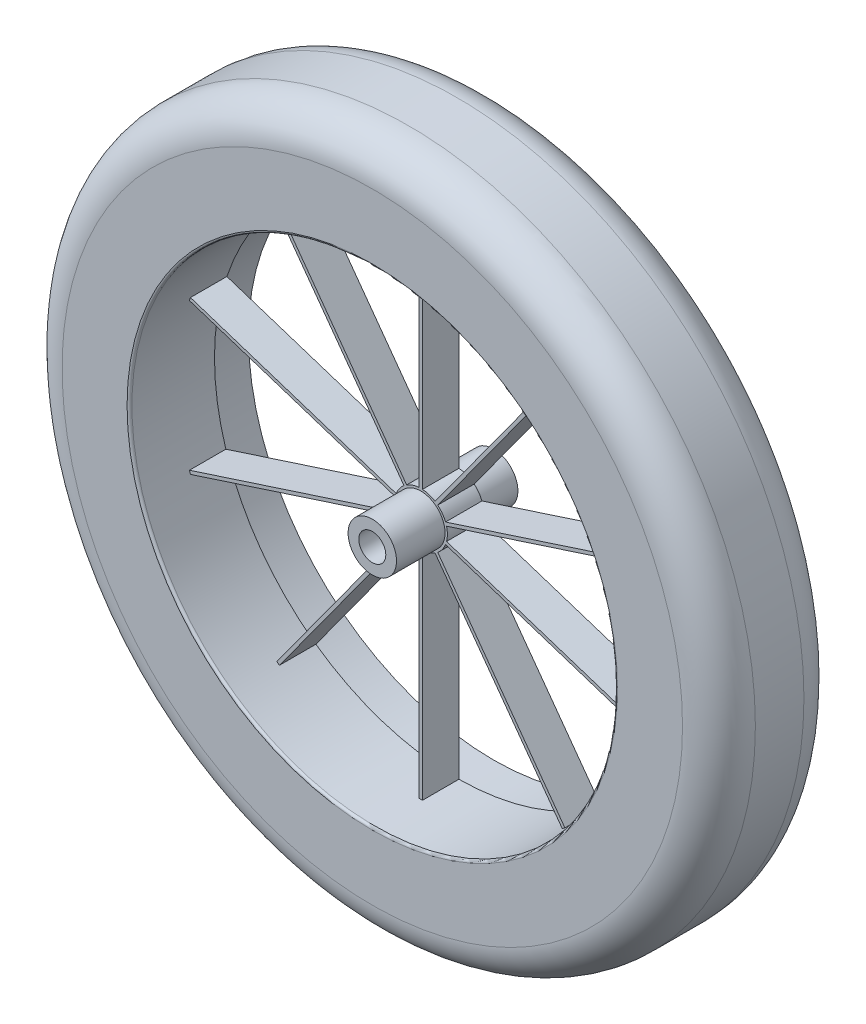
SolidWorks part; units mm, degrees
ref_plane "Alzado" through (0, 0, 0) normal (0, 0, 1) x (1, 0, 0)
ref_plane "Planta" through (0, 0, 0) normal (0, 1, 0) x (1, 0, 0)
ref_plane "Vista lateral" through (0, 0, 0) normal (1, 0, 0) x (0, 0, -1)
sketch "Croquis1" plane through (0, 0, 0) normal (0, 0, 1) x (1, 0, 0)
  circle A0 centre (0, 0) radius 275
  dimension "D1" = 550
extrude "Saliente-Extruir1" add sketch "Croquis1" along normal blind 70
sketch "Croquis2" plane through (0, 0, 70) normal (0, 0, 1) x (1, 0, 0)
  circle A0 centre (0, 0) radius 200
  dimension "D1" = 400
extrude "Cortar-Extruir1" cut sketch "Croquis2" against normal blind 40
sketch "Croquis5" plane through (0, 0, 30) normal (0, 0, 1) x (1, 0, 0)
  circle A0 centre (0, 0) radius 10
  dimension "D1" = 20
extrude "Cortar-Extruir2" cut sketch "Croquis5" against normal blind 10
fillet "Redondeo1" radius 2 1 edges at (200, 0, 70)
sketch "Croquis6" plane through (0, 0, 70) normal (0, 0, 1) x (1, 0, 0)
  line L0 (0, 275) -> (0, 247)
  line L1 (99.3415, 256.4299) -> (89.2267, 230.3206)
  line L2 (185.2663, 203.2275) -> (166.4028, 182.5352)
  line L3 (246.1699, 122.578) -> (221.1053, 110.0974)
  line L4 (273.8269, 25.3738) -> (245.9463, 22.7903)
  line L5 (264.5021, -75.2573) -> (237.5709, -67.5948)
  line L6 (219.4547, -165.7245) -> (197.1103, -148.8508)
  line L7 (144.7688, -233.8097) -> (130.0287, -210.0036)
  line L8 (50.5311, -270.3176) -> (45.3861, -242.7944)
  line L9 (-50.5311, -270.3176) -> (-45.3861, -242.7944)
  line L10 (-144.7688, -233.8097) -> (-130.0287, -210.0036)
  line L11 (-219.4547, -165.7245) -> (-197.1103, -148.8508)
  line L12 (-264.5021, -75.2573) -> (-237.5709, -67.5948)
  line L13 (-273.8269, 25.3738) -> (-245.9463, 22.7903)
  line L14 (-246.1699, 122.578) -> (-221.1053, 110.0974)
  line L15 (-185.2663, 203.2275) -> (-166.4028, 182.5352)
  line L16 (-99.3415, 256.4299) -> (-89.2267, 230.3206)
  circle A0 centre (0, 0) radius 275 construction
  point P40 (0, 0)
  dimension "D2" = 28
  dimension "D1" = 17
extrude "Cortar-Extruir-Lámina2" cut sketch "Croquis6" against normal through all thin contours L16
pattern_circular "MatrizC1" count 24 every 15 about axis through (0, 0, 0) along (0, 0, 1) of "Cortar-Extruir-Lámina2"
sketch "Croquis11" plane through (0, 0, 30) normal (0, 0, 1) x (1, 0, 0)
  line L0 (207.6044, 68.8646) -> (-208.433, -66.3142)
  line L1 (-1.3408, 218.7238) -> (1.3408, 218.7238)
  line L2 (-1.3408, 218.7238) -> (-1.3408, -218.7238)
  line L3 (-1.3408, -218.7238) -> (1.3408, -218.7238)
  line L4 (1.3408, 218.7238) -> (1.3408, -218.7238)
  line L5 (-1.3408, 218.7238) -> (1.3408, -218.7238) construction
  line L6 (-1.3408, -218.7238) -> (1.3408, 218.7238) construction
  line L7 (208.433, 66.3142) -> (-207.6044, -68.8646)
  line L8 (129.6474, -176.1632) -> (-127.4779, 177.7394)
  line L9 (127.4779, -177.7394) -> (-129.6474, 176.1632)
  line L10 (-127.4779, -177.7394) -> (129.6474, 176.1632)
  line L11 (-129.6474, -176.1632) -> (127.4779, 177.7394)
  line L12 (-208.433, 66.3142) -> (207.6044, -68.8646)
  line L13 (-207.6044, 68.8646) -> (208.433, -66.3142)
  circle A0 centre (0, 0) radius 21.8489
  circle A1 centre (0, 0) radius 200 construction
  circle A2 centre (0, 0) radius 200
  point P27 (0, 0)
  circle M2 centre (0, 0) radius 200
  dimension "D1" = 5
extrude "Cortar-Extruir3" cut sketch "Croquis11" against normal blind 150 contours A0 L9 L13 M2 | A0 L2 L8 M2 | A0 L11 L4 M2 | A0 L0 L10 M2 | A0 L13 L7 M2 | A0 L8 L12 M2 | A0 L12 L0 M2 | A0 L7 L11 M2 | A0 L10 L2 M2 | A0 L4 L9 M2
sketch "Croquis12" plane through (0, 0, 20) normal (0, 0, 1) x (1, 0, 0)
  circle A3 centre (0, 0) radius 19.935
extrude "Saliente-Extruir2" add sketch "Croquis12" along normal blind 50 and the other way blind 50
sketch "Croquis14" plane through (0, 0, 70) normal (0, 0, 1) x (1, 0, 0)
  circle A0 centre (0, 0) radius 285.5468
  circle A1 centre (0, 0) radius 202 construction
  circle A2 centre (0, 0) radius 202
extrude "Saliente-Extruir3" add sketch "Croquis14" against normal blind 100
fillet "Redondeo2" radius 30 1 edges at (285.5468, 0, 70)
fillet "Redondeo3" radius 30 1 edges at (285.5468, 0, -30)
scale "Scale1" scale about centroid uniform scaling yes scale factor 0.5
scale "Scale2" scale about centroid uniform scaling yes scale factor 0.1
scale "Scale3" scale about centroid uniform scaling yes scale factor 0.2
scale "Scale4" scale about centroid uniform scaling yes scale factor 0.3
scale "Scale5" scale about centroid uniform scaling yes scale factor 20
scale "Scale6" scale about centroid uniform scaling yes scale factor 1.5
sketch "Sketch1" plane through (0, 0, 24.6335) normal (0, 0, 1) x (1, 0, 0)
  circle A0 centre (0, 0) radius 1
  dimension "D1" = 2
extrude "Cut-Extrude1" cut sketch "Sketch1" against normal blind 5
